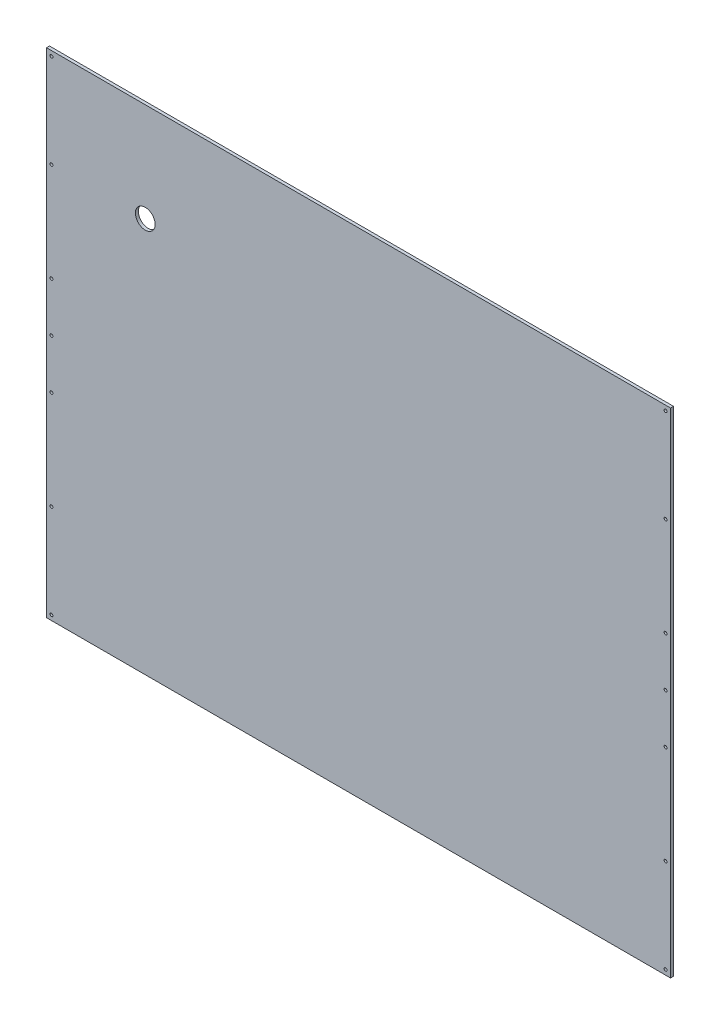
SolidWorks part; units mm, degrees
ref_plane "前视基准面" through (0, 0, 0) normal (0, 0, 1) x (1, 0, 0)
ref_plane "上视基准面" through (0, 0, 0) normal (0, 1, 0) x (1, 0, 0)
ref_plane "右视基准面" through (0, 0, 0) normal (1, 0, 0) x (0, 0, -1)
sketch "草图1" plane through (0, 0, 0) normal (0, 0, 1) x (1, 0, 0)
  line L0 (627, 537.5875) -> (627, -65.4008) construction
  line L1 (0, 0) -> (632, 0)
  line L2 (0, 0) -> (0, 500)
  line L3 (0, 500) -> (632, 500)
  line L4 (632, 0) -> (632, 500)
  line L5 (632, 250) -> (-43.4407, 250) construction
  line L6 (316, 500) -> (316, 184.5786) construction
  circle A0 centre (627, 250) radius 1.5
  circle A1 centre (627, 300) radius 1.5
  circle A3 centre (627, 400) radius 1.5
  circle A5 centre (627, 495) radius 1.5
  circle A6 centre (627, 5) radius 1.5
  circle A7 centre (627, 100) radius 1.5
  circle A8 centre (627, 200) radius 1.5
  circle A9 centre (5, 200) radius 1.5
  circle A10 centre (5, 100) radius 1.5
  circle A11 centre (5, 5) radius 1.5
  circle A12 centre (5, 495) radius 1.5
  circle A13 centre (5, 400) radius 1.5
  circle A14 centre (5, 300) radius 1.5
  circle A15 centre (5, 250) radius 1.5
  circle A16 centre (100, 400) radius 10
  dimension "D4" = 100
  dimension "D8" = 5
  dimension "D6" = 20
  dimension "D1" = 500
  dimension "D2" = 632
  dimension "D3" = 5
  dimension "D5" = 100
  dimension "D7" = 100
  dimension "D9" = 100
extrude "凸台-拉伸1" add sketch "草图1" along normal blind 3
